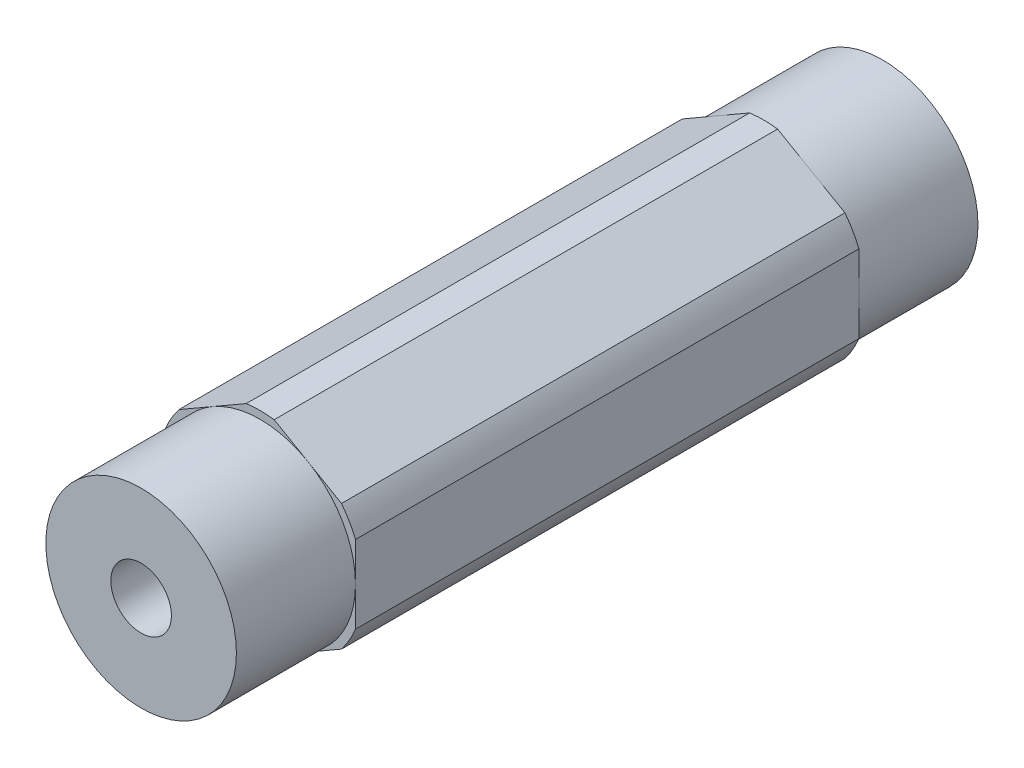
SolidWorks part; units mm, degrees
ref_plane "Front Plane" through (0, 0, 0) normal (0, 0, 1) x (1, 0, 0)
ref_plane "Top Plane" through (0, 0, 0) normal (0, 1, 0) x (1, 0, 0)
ref_plane "Right Plane" through (0, 0, 0) normal (1, 0, 0) x (0, 0, -1)
sketch "Sketch1" plane through (0, 0, 0) normal (0, 0, 1) x (1, 0, 0)
  line L1 (0, 7.3323) -> (-6.35, 3.6662)
  line L2 (-6.35, 3.6662) -> (-6.35, -3.6662)
  line L3 (-6.35, -3.6662) -> (0, -7.3323)
  line L4 (0, -7.3323) -> (6.35, -3.6662)
  line L5 (6.35, -3.6662) -> (6.35, 3.6662)
  line L6 (6.35, 3.6662) -> (0, 7.3323)
  circle A0 centre (0, 0) radius 6.35 construction
  circle A1 centre (0, 0) radius 6.858
  dimension "D1" = 12.7
  dimension "D2" = 13.716
extrude "Boss-Extrude1" add sketch "Sketch1" along normal mid plane 33.5509 contours L5 A1 L6 L1 L2 L3 L4
sketch "Sketch4" plane through (0, 0, 16.7754) normal (0, 0, 1) x (1, 0, 0)
  line L0 (5.4183, 4.2041) -> (0.9317, 6.7944) construction
  circle A0 centre (0, 0) radius 6.35
extrude "Boss-Extrude2" add sketch "Sketch4" along normal blind 7.9375
mirror "Mirror1" about plane through (0, 0, 0) normal (0, 0, 1) of "Boss-Extrude2"
hole_wizard "#10-32 Tapped Hole1" positions "3DSketch3" profile "Sketch7" tap size "#10-32" standard "ANSI Inch"
sketch3d "3DSketch3"
  line L0 (0, 0, 24.7129) -> (0, 0, 16.7754) construction
  line L1 (0, 0, -24.7129) -> (0, 0, -16.7754) construction
  point P0 (0, 0, 24.7129)
  point P4 (0, 0, -24.7129)
sketch "Sketch7" plane through (0, 0, 24.7129) normal (1, 0, 0) x (0, -1, 0)
  line L0 (0, 0) -> (0, 13.2428)
  line L1 (0, 13.2428) -> (2.0193, 12.0294)
  line L2 (2.0193, 12.0294) -> (2.0193, 0)
  line L5 (2.0193, 0) -> (0, 0)
  line L10 (0, 13.2428) -> (-2.0193, 12.0294) construction
  line L11 (0, -6.35) -> (0, 107.95) construction
  dimension "Tap Drill Dia." = 4.0386
  dimension "Tap Drill Depth" = 12.0294
  dimension "Drill Angle" = 118
cosmetic thread "Hole Thread1" parameters "D1"=9.652, "D2"=4.826
cosmetic thread "Hole Thread2" parameters "D1"=9.652, "D2"=4.826
